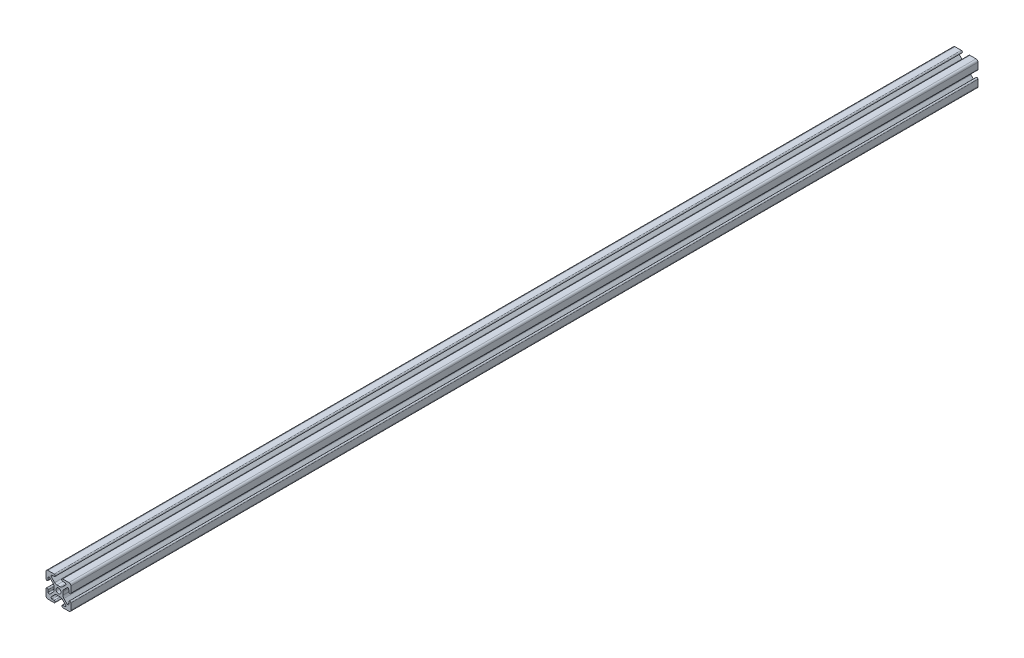
SolidWorks part; units mm, degrees
material "6061 Alloy"
ref_plane "Front Plane" through (0, 0, 0) normal (0, 0, 1) x (1, 0, 0)
ref_plane "Top Plane" through (0, 0, 0) normal (0, 1, 0) x (1, 0, 0)
ref_plane "Right Plane" through (0, 0, 0) normal (1, 0, 0) x (0, 0, -1)
sketch "Sketch1" plane through (0, 0, 0) normal (0, 0, 1) x (1, 0, 0)
  line L0 (-8.6363, 7.1116) -> (-5.4322, 3.9121)
  line L1 (-4.455, 1.5554) -> (-4.455, -1.5554)
  line L2 (-5.4322, -3.9121) -> (-8.6363, -7.1116)
  line L3 (-10.36, -6.3969) -> (-10.36, -4.32)
  line L4 (-12.5, -4.32) -> (-12.5, -8.6518)
  line L5 (-12.5, -8.6518) -> (-12.5, -10.5371)
  line L6 (-10.5371, -12.5) -> (-8.4416, -12.5)
  line L7 (-8.4416, -12.5) -> (-4.3879, -12.5)
  line L8 (-4.3879, -10.36) -> (-6.42, -10.36)
  line L9 (-7.1337, -8.6353) -> (-3.7953, -5.3018)
  line L10 (-1.5554, -4.375) -> (1.5554, -4.375)
  line L11 (10.36, 4.32) -> (10.36, 6.3969)
  line L12 (12.5, 7.9913) -> (12.5, 4.32)
  line L13 (12.5, 10.5371) -> (12.5, 7.9913)
  line L14 (4.32, 12.5) -> (10.5371, 12.5)
  line L16 (6.42, 10.36) -> (4.32, 10.36)
  line L17 (3.7953, 5.3018) -> (7.1337, 8.6353)
  line L18 (7.1337, -8.6353) -> (3.7953, -5.3018)
  line L19 (4.3879, -10.36) -> (6.42, -10.36)
  line L20 (8.4416, -12.5) -> (4.3879, -12.5)
  line L21 (10.5371, -12.5) -> (8.4416, -12.5)
  line L22 (12.5, -8.6518) -> (12.5, -10.5371)
  line L23 (12.5, -4.32) -> (12.5, -8.6518)
  line L24 (10.36, -6.3969) -> (10.36, -4.32)
  line L25 (5.4322, -3.9121) -> (8.6363, -7.1116)
  line L26 (4.455, 1.5554) -> (4.455, -1.5554)
  line L27 (8.6363, 7.1116) -> (5.4322, 3.9121)
  line L28 (1.5554, 4.375) -> (-1.5554, 4.375)
  line L29 (-3.7953, 5.3018) -> (-7.1337, 8.6353)
  line L30 (-6.42, 10.36) -> (-4.32, 10.36)
  line L32 (-4.32, 12.5) -> (-10.5371, 12.5)
  line L33 (-12.5, 10.5371) -> (-12.5, 7.9913)
  line L34 (-12.5, 7.9913) -> (-12.5, 4.32)
  line L35 (-10.36, 4.32) -> (-10.36, 6.3969)
  line L36 (-15.7693, 0) -> (12.5, 0) construction
  line L37 (0, 13.9334) -> (0, -12.3541) construction
  circle A0 centre (0, 0) radius 2.5
  arc A1 (-8.6363, 7.1116) -> (-10.36, 6.3969) centre (-9.35, 6.3969) ccw
  arc A2 (-4.455, 1.5554) -> (-5.4322, 3.9121) centre (-7.7855, 1.5554) ccw
  arc A3 (-5.4322, -3.9121) -> (-4.455, -1.5554) centre (-7.7855, -1.5554) ccw
  arc A4 (-10.36, -6.3969) -> (-8.6363, -7.1116) centre (-9.35, -6.3969) ccw
  arc A5 (-10.36, -4.32) -> (-12.5, -4.32) centre (-11.43, -4.32) ccw
  arc A6 (-12.5, -10.5371) -> (-10.5371, -12.5) centre (-10.5371, -10.5371) ccw
  arc A7 (-4.3879, -12.5) -> (-4.3879, -10.36) centre (-4.3879, -11.43) ccw
  arc A8 (-7.1337, -8.6353) -> (-6.42, -10.36) centre (-6.42, -9.35) ccw
  arc A9 (-1.5554, -4.375) -> (-3.7953, -5.3018) centre (-1.5554, -7.545) ccw
  arc A10 (12.5, 4.32) -> (10.36, 4.32) centre (11.43, 4.32) cw
  arc A11 (10.5371, 12.5) -> (12.5, 10.5371) centre (10.5371, 10.5371) cw
  arc A12 (4.32, 10.36) -> (4.32, 12.5) centre (4.32, 11.43) cw
  arc A13 (6.42, 10.36) -> (7.1337, 8.6353) centre (6.42, 9.35) cw
  arc A14 (3.7953, 5.3018) -> (1.5554, 4.375) centre (1.5554, 7.545) cw
  arc A15 (1.5554, -4.375) -> (3.7953, -5.3018) centre (1.5554, -7.545) cw
  arc A16 (7.1337, -8.6353) -> (6.42, -10.36) centre (6.42, -9.35) cw
  arc A17 (4.3879, -12.5) -> (4.3879, -10.36) centre (4.3879, -11.43) cw
  arc A18 (12.5, -10.5371) -> (10.5371, -12.5) centre (10.5371, -10.5371) cw
  arc A19 (10.36, -4.32) -> (12.5, -4.32) centre (11.43, -4.32) cw
  arc A20 (10.36, -6.3969) -> (8.6363, -7.1116) centre (9.35, -6.3969) cw
  arc A21 (5.4322, -3.9121) -> (4.455, -1.5554) centre (7.7855, -1.5554) cw
  arc A22 (4.455, 1.5554) -> (5.4322, 3.9121) centre (7.7855, 1.5554) cw
  arc A23 (8.6363, 7.1116) -> (10.36, 6.3969) centre (9.35, 6.3969) cw
  arc A24 (-3.7953, 5.3018) -> (-1.5554, 4.375) centre (-1.5554, 7.545) ccw
  arc A25 (-6.42, 10.36) -> (-7.1337, 8.6353) centre (-6.42, 9.35) ccw
  arc A26 (-4.32, 10.36) -> (-4.32, 12.5) centre (-4.32, 11.43) ccw
  arc A27 (-10.5371, 12.5) -> (-12.5, 10.5371) centre (-10.5371, 10.5371) ccw
  arc A28 (-12.5, 4.32) -> (-10.36, 4.32) centre (-11.43, 4.32) ccw
  dimension "D4" = 14.86
  dimension "D5" = 2.14
  dimension "D6" = 6.5
  dimension "D7" = 8.75
  dimension "D8" = 1.01
  dimension "D9" = 3.17
  dimension "D14" = 5
  dimension "D1" = 25
  dimension "D2" = 8.91
  dimension "D3" = 12.5
  dimension "D12" = 2.14
extrude "Extrude1" add sketch "Sketch1" against normal blind 911
